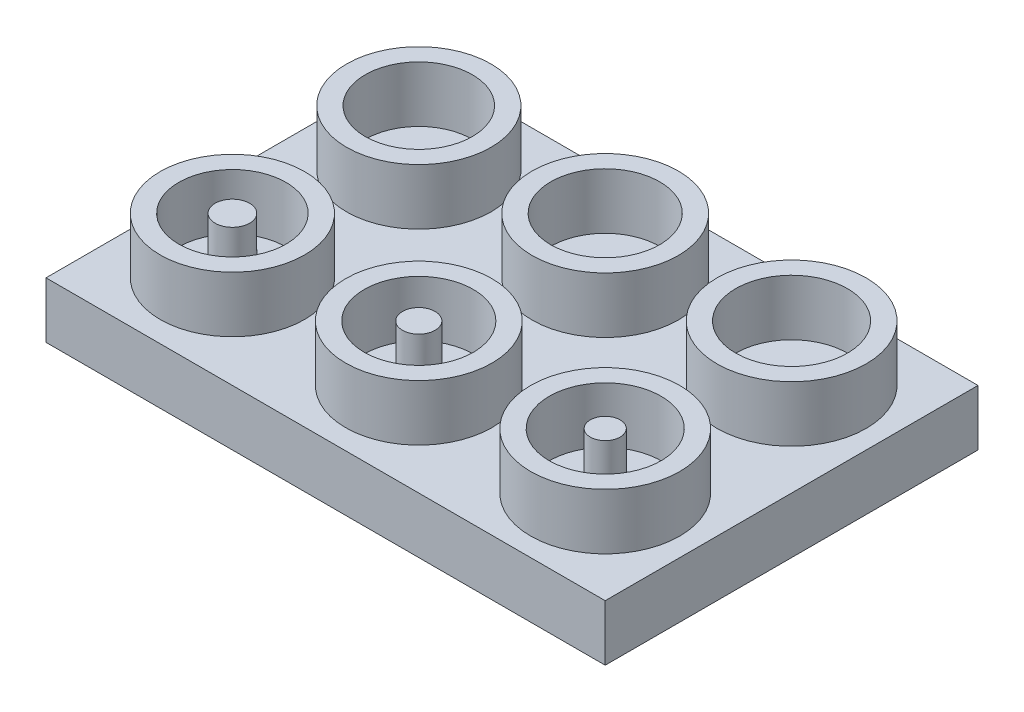
SolidWorks part; units mm, degrees
ref_plane "Front Plane" through (0, 0, 0) normal (0, 0, 1) x (1, 0, 0)
ref_plane "Top Plane" through (0, 0, 0) normal (0, 1, 0) x (1, 0, 0)
ref_plane "Right Plane" through (0, 0, 0) normal (1, 0, 0) x (0, 0, -1)
sketch "Sketch1" plane through (0, 0, 0) normal (0, 1, 0) x (1, 0, 0)
  line L1 (-15, -10) -> (15, -10)
  line L2 (-15, -10) -> (-15, 10)
  line L3 (-15, 10) -> (15, 10)
  line L4 (15, -10) -> (15, 10)
  line L5 (-15, -10) -> (15, 10) construction
  line L6 (-15, 10) -> (15, -10) construction
  point P0 (0, 0)
  dimension "D1" = 20
  dimension "D2" = 30
extrude "Boss-Extrude1" add sketch "Sketch1" along normal blind 3
sketch "Sketch3" plane through (0, 3, 0) normal (0, 1, 0) x (1, 0, 0)
  line L0 (-10, -5) -> (0, -5) construction
  line L1 (-10, -5) -> (-10, 5) construction
  point P0 (-10, -5)
  point P1 (0, -5)
  point P2 (-10.9134, 4.5789)
  point P3 (-10, 0)
  point P4 (10, -5)
  point P5 (0, 5)
  point P6 (10, 5)
  point P7 (-10, 5)
  point P12 (0, 0)
  point P13 (0, 0)
  point P14 (0, 0)
  point P15 (0, 0)
  dimension "D1" = 3
  dimension "D2" = 2
  dimension "D3" = 10
  dimension "D4" = 10
sketch "Sketch2" plane through (0, 3, 0) normal (0, 1, 0) x (1, 0, 0)
  circle A0 centre (-10, 5) radius 2.875
  circle A1 centre (0, 5) radius 2.925
  circle A2 centre (10, 5) radius 3
  circle A3 centre (-10, -5) radius 2.875
  circle A4 centre (0, -5) radius 2.925
  circle A5 centre (10, -5) radius 3
  circle A6 centre (-10, 5) radius 3.875
  circle A7 centre (0, 5) radius 3.925
  circle A8 centre (10, 5) radius 4
  circle A9 centre (10, -5) radius 4
  circle A10 centre (0, -5) radius 3.925
  circle A11 centre (-10, -5) radius 3.875
  circle A12 centre (-10, -5) radius 0.925
  circle A13 centre (0, -5) radius 0.875
  circle A14 centre (10, -5) radius 0.8
  point P33 (0, 0)
  point P34 (0, 0)
  dimension "D1" = 5.75
  dimension "D2" = 5.85
  dimension "D3" = 6
  dimension "D4" = 5.75
  dimension "D5" = 5.85
  dimension "D6" = 6
  dimension "D8" = 1.85
  dimension "D9" = 1.75
  dimension "D10" = 1.6
  dimension "D7" = 1
extrude "Boss-Extrude2" add sketch "Sketch2" along normal blind 3 contours A6 A0 | A7 A1 | A8 A2 | A11 A3 | A12 | A13 | A10 A4 | A9 A5 | A14
sketch "Sketch4" plane through (0, 0, 0) normal (0, -1, 0) x (-1, 0, 0)
  line L0 (10, -10) -> (10, 10) construction
  line L1 (15, -10) -> (-15, -10) construction
  line L2 (-15, 10) -> (15, 10) construction
  line L3 (15, 10) -> (15, -10) construction
  line L4 (-10, -10) -> (-10, 10) construction
  line L5 (-15, -10) -> (-15, 10) construction
  line L6 (0, -10) -> (0, 10) construction
  text T0 "LOW 0"
  text T1 "HI 0.25"
  text T2 "MID 0.1"
  dimension "D1" = 5
  dimension "D2" = 5
extrude "Cut-Extrude1" cut sketch "Sketch4" against normal blind 2
equation "\"D2@Sketch2\"=\"D1@Sketch2\"+0.1"
equation "\"D3@Sketch2\"=\"D1@Sketch2\"+0.25"
equation "\"D4@Sketch2\"=\"D1@Sketch2\""
equation "\"D5@Sketch2\"=\"D2@Sketch2\""
equation "\"D6@Sketch2\"=\"D3@Sketch2\""
equation "\"D9@Sketch2\"=\"D8@Sketch2\"-0.1"
equation "\"D10@Sketch2\"=\"D8@Sketch2\"-0.25"
